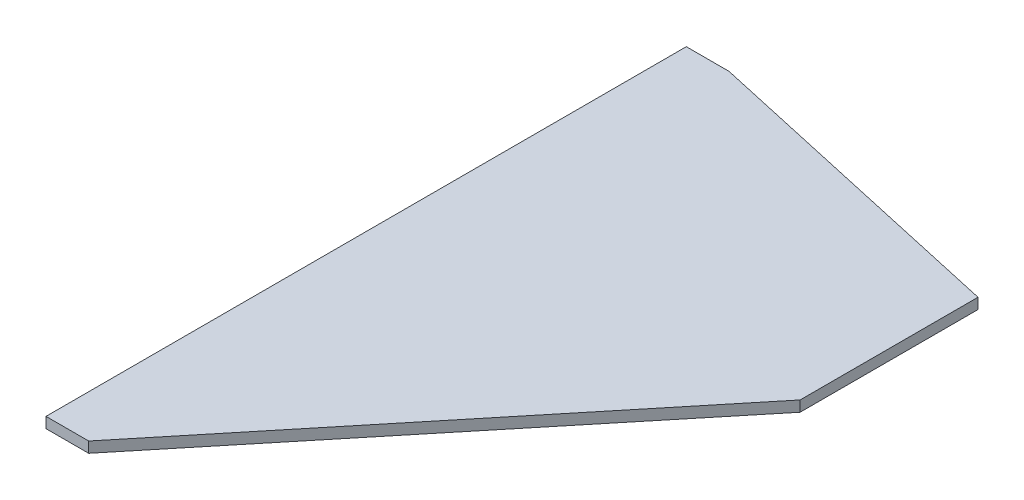
SolidWorks part; units mm, degrees
ref_plane "Front Plane" through (0, 0, 0) normal (0, 0, 1) x (1, 0, 0)
ref_plane "Top Plane" through (0, 0, 0) normal (0, 1, 0) x (1, 0, 0)
ref_plane "Right Plane" through (0, 0, 0) normal (1, 0, 0) x (0, 0, -1)
sketch "Sketch1" plane through (0, 0, 0) normal (0, 1, 0) x (1, 0, 0)
  line L0 (12, 0) -> (102, 110)
  line L1 (0, 0) -> (12, 0)
  line L2 (0, 0) -> (0, 180)
  line L3 (0, 180) -> (12, 180)
  line L5 (102, 110) -> (102, 160)
  line L6 (102, 160) -> (12, 180)
  dimension "D1" = 110
  dimension "D2" = 50
  dimension "D3" = 180
  dimension "D4" = 12
  dimension "D5" = 90
  dimension "D6" = 12
extrude "Boss-Extrude1" add sketch "Sketch1" along normal blind 3
